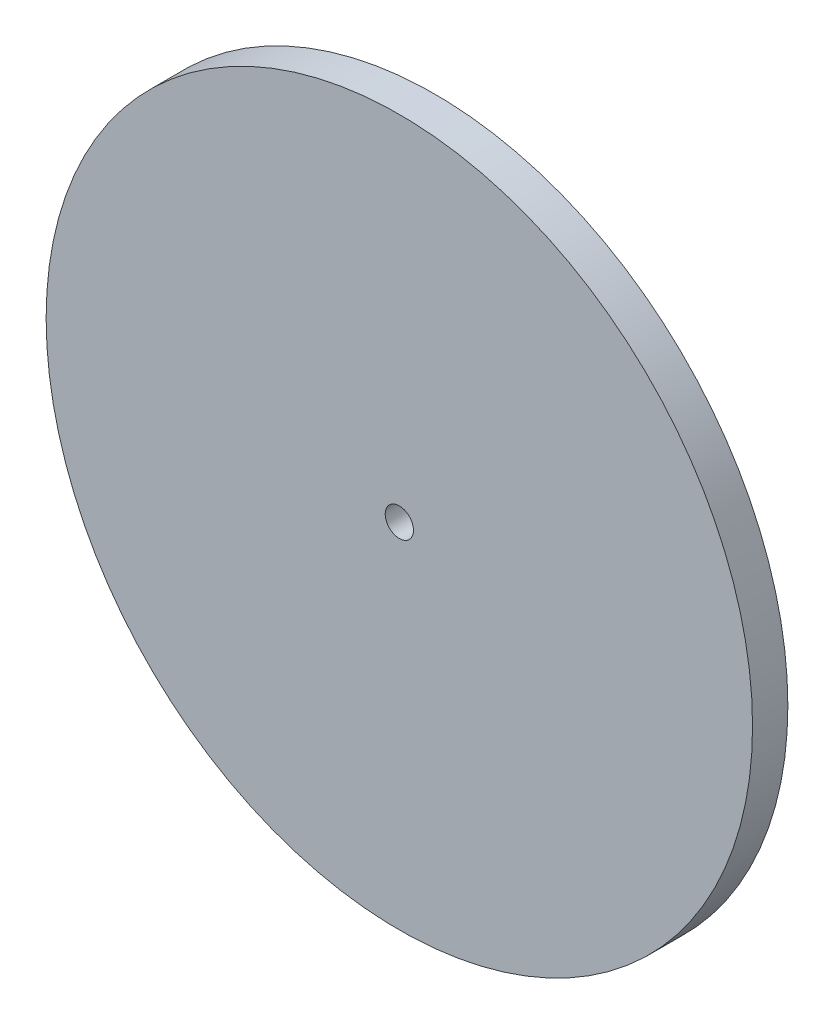
SolidWorks part; units mm, degrees
ref_plane "Front Plane" through (0, 0, 0) normal (0, 0, 1) x (1, 0, 0)
ref_plane "Top Plane" through (0, 0, 0) normal (0, 1, 0) x (1, 0, 0)
ref_plane "Right Plane" through (0, 0, 0) normal (1, 0, 0) x (0, 0, -1)
sketch "Sketch1" plane through (0, 0, 0) normal (0, 0, 1) x (1, 0, 0)
  circle A0 centre (0, 0) radius 100
  circle A1 centre (0, 0) radius 4
  dimension "D1" = 200
  dimension "D2" = 8
extrude "Boss-Extrude1" add sketch "Sketch1" along normal blind 10
